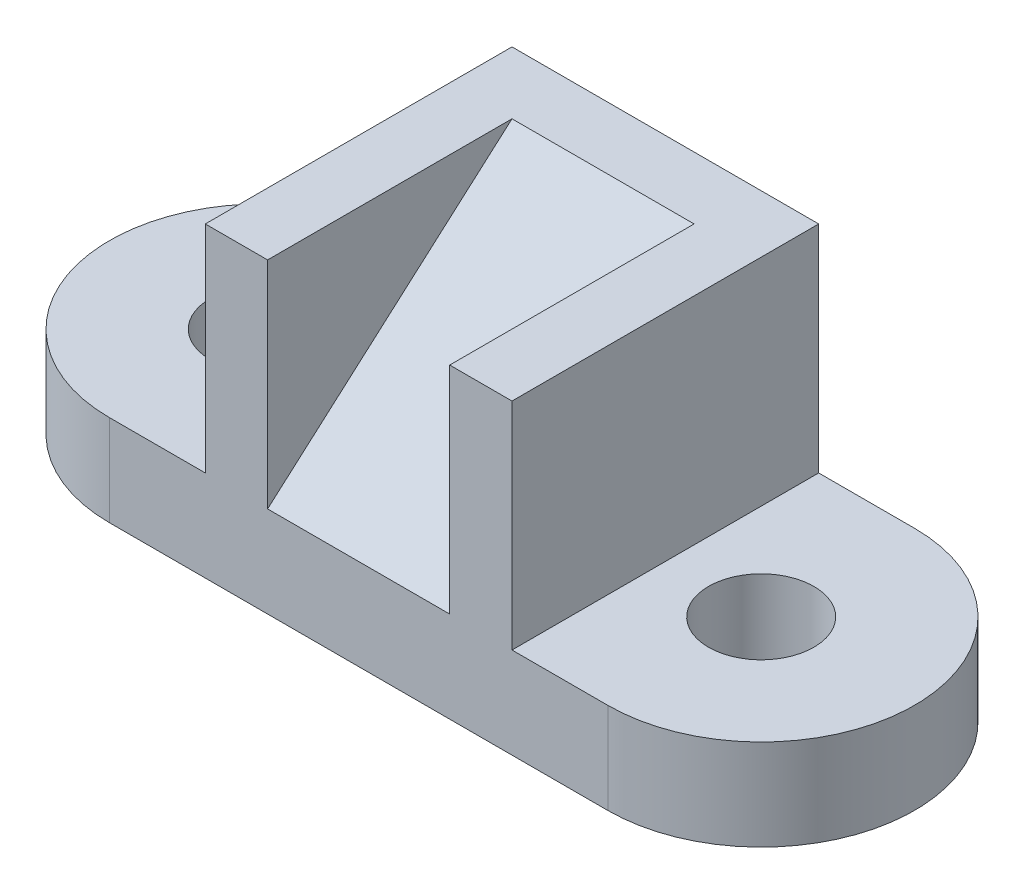
SolidWorks part; units mm, degrees
ref_plane "정면" through (0, 0, 0) normal (0, 0, 1) x (1, 0, 0)
ref_plane "윗면" through (0, 0, 0) normal (0, 1, 0) x (1, 0, 0)
ref_plane "우측면" through (0, 0, 0) normal (1, 0, 0) x (0, 0, -1)
sketch "스케치2" plane through (0, 0, 0) normal (0, 1, 0) x (1, 0, 0)
  line L0 (0, 0) -> (0, 83.7726) construction
  line L2 (0, 0) -> (104, 0)
  line L3 (0, 0) -> (0, 64)
  line L4 (0, 64) -> (104, 64)
  line L5 (104, 0) -> (104, 64)
  arc A0 (104, 0) -> (104, 64) centre (104, 32) ccw
  arc A1 (0, 64) -> (0, 0) centre (0, 32) ccw
  circle A2 centre (0, 32) radius 11
  circle A3 centre (104, 32) radius 11
  point P7 (0, 0)
  dimension "D1" = 104
  dimension "D2" = 64
extrude "보스-돌출1" add sketch "스케치2" along normal blind 19 contours A3 L5 L4 L3 A2 L2 | A2 L3 A1 | A3 L5 A0
sketch "스케치3" plane through (0, 19, 0) normal (0, 1, 0) x (1, 0, 0)
  line L0 (52, 0) -> (52, 68.5957) construction
  line L1 (0, 0) -> (104, 0) construction
  line L2 (84, 0) -> (84, 64)
  line L3 (0, 64) -> (104, 64) construction
  line L4 (20, 0) -> (20, 64)
  line L5 (84, 64) -> (20, 64)
  line L6 (84, 0) -> (71, 0)
  line L7 (20, 0) -> (33, 0)
  line L8 (71, 0) -> (71, 51)
  line L9 (33, 0) -> (33, 51)
  line L10 (71, 51) -> (33, 51)
  point P10 (52, 64)
  point P15 (52, 51)
  dimension "D1" = 64
  dimension "D2" = 38
  dimension "D3" = 51
extrude "보스-돌출2" add sketch "스케치3" along normal blind 45
sketch "스케치6" plane through (33, 0, 0) normal (1, 0, 0) x (0, 0, -1)
  line L0 (51, 64) -> (0, 19)
  line L1 (0, 19) -> (51, 19)
  line L2 (51, 19) -> (51, 64)
extrude "보스-돌출3" add sketch "스케치6" along normal blind 38 contours L2 L0 L1
